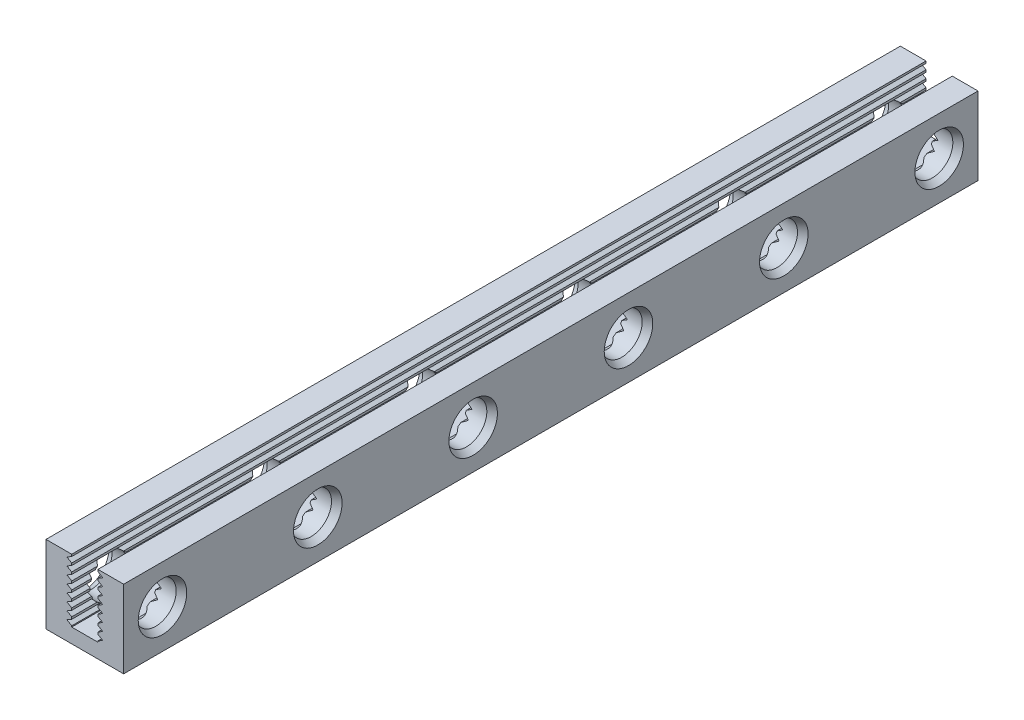
SolidWorks part; units mm, degrees
material "Alliage 6061"
ref_plane "Face" through (0, 0, 0) normal (0, 0, 1) x (1, 0, 0)
ref_plane "Dessus" through (0, 0, 0) normal (0, 1, 0) x (1, 0, 0)
ref_plane "Droite" through (0, 0, 0) normal (1, 0, 0) x (0, 0, -1)
sketch "Esquisse1" plane through (0, 0, 0) normal (0, 0, 1) x (1, 0, 0)
  line L0 (0, 4) -> (0, -4) construction
  line L1 (-4, 4) -> (-1.35, 4)
  line L2 (-4, 4) -> (-4, -4)
  line L3 (-4, -4) -> (4, -4)
  line L4 (4, 4) -> (4, -4)
  line L5 (-1.35, 4) -> (-1.35, -2.5)
  line L6 (-1.35, -2.5) -> (1.35, -2.5)
  line L7 (1.35, -2.5) -> (1.35, 4)
  line L8 (1.35, 4) -> (4, 4)
  line L9 (-4, 0) -> (4, 0) construction
  dimension "D1" = 8
  dimension "D2" = 8
  dimension "D3" = 1.5
  dimension "D4" = 2.7
extrude "Boss.-Extru.1" add sketch "Esquisse1" along normal blind 88
sketch "Esquisse2" plane through (0, 0, 88) normal (0, 0, 1) x (1, 0, 0)
  line L0 (-1.35, -2.0963) -> (-2.35, -2.0963) construction
  line L1 (-1.35, -2.5) -> (-1.35, 4) construction
  line L2 (-1.35, -1.8076) -> (-1.85, -2.0963)
  line L3 (-1.85, -2.0963) -> (-1.35, -2.385)
  line L4 (-1.35, -2.385) -> (-1.35, -1.8076)
  dimension "D1" = 60
  dimension "D2" = 0.5
  dimension "D3" = 0.115
extrude "Enlèv. mat.-Extru.1" cut sketch "Esquisse2" against normal through all
pattern_linear "Répétition linéaire1" count 8 spacing 0.8 along (0, 1, 0) of "Enlèv. mat.-Extru.1"
mirror "Symétrie1" about plane through (0, 0, 0) normal (1, 0, 0) of "Répétition linéaire1", "Enlèv. mat.-Extru.1"
hole_wizard "Dégagement M41" positions "Esquisse4" profile "Esquisse3" hole size "M4" standard "Iso" end condition through all
sketch "Esquisse4" plane through (-4, 0, 0) normal (-1, 0, 0) x (0, 0, 1)
  line L0 (44, 4) -> (44, -4) construction
  line L1 (88, 4) -> (0, 4) construction
  line L2 (88, -4) -> (0, -4) construction
  line L3 (0, 0) -> (88, 0) construction
  line L4 (0, 4) -> (0, -4) construction
  line L5 (88, 4) -> (88, -4) construction
  point P0 (4, 0)
  point P2 (20, 0)
  point P4 (36, 0)
  point P6 (52, 0)
  point P8 (68, 0)
  point P10 (84, 0)
  dimension "D1" = 16
  dimension "D2" = 16
  dimension "D3" = 16
  dimension "D4" = 16
  dimension "D5" = 16
sketch "Esquisse3" plane through (-4, 0, 4) normal (0, 1, 0) x (0, 0, 1)
  line L0 (0, 0) -> (0, 8)
  line L1 (0, 8) -> (2.5, 8)
  line L2 (2.1, 7.3072) -> (2.1, 0.6928)
  line L3 (2.1, 0.6928) -> (2.5, 0)
  line L5 (2.5, 0) -> (0, 0)
  line L6 (-2.1, 0.6928) -> (-2.5, 0) construction
  line L7 (2.5, 8) -> (2.1, 7.3072)
  line L8 (-2.5, 8) -> (-2.1, 7.3072) construction
  line L11 (0, -6.35) -> (0, 107.95) construction
  dimension "Diamètre du perçage jusqu'au prochain" = 4.2
  dimension "Profondeur du perçage jusqu'au prochain" = 8
  dimension "Diamètre du fraisage entrant" = 5
  dimension "Angle du fraisage entrant" = 60
  dimension "Diamètre du fraisage débouchant" = 5
  dimension "Angle du fraisage débouchant" = 60
